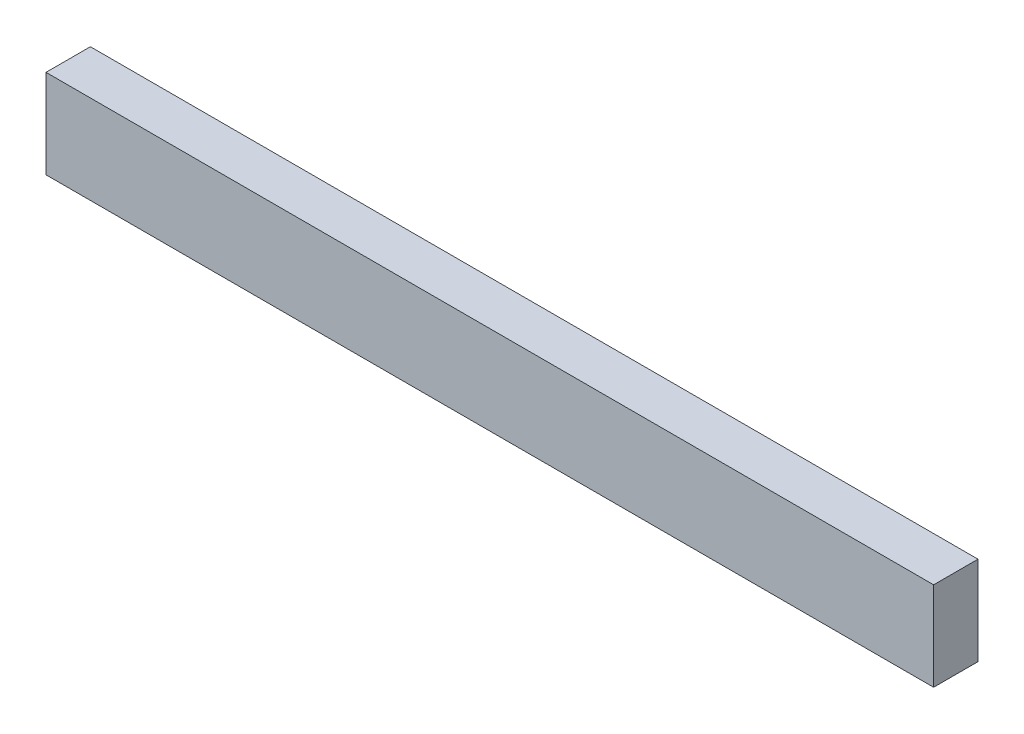
SolidWorks part; units mm, degrees
ref_plane "Front Plane" through (0, 0, 0) normal (0, 0, 1) x (1, 0, 0)
ref_plane "Top Plane" through (0, 0, 0) normal (0, 1, 0) x (1, 0, 0)
ref_plane "Right Plane" through (0, 0, 0) normal (1, 0, 0) x (0, 0, -1)
sketch "Эскиз1" plane through (0, 0, 0) normal (0, 0, 1) x (1, 0, 0)
  line L1 (-10, -1) -> (10, -1)
  line L2 (-10, -1) -> (-10, 1)
  line L3 (-10, 1) -> (10, 1)
  line L4 (10, -1) -> (10, 1)
  line L5 (-10, -1) -> (10, 1) construction
  line L6 (-10, 1) -> (10, -1) construction
  point P0 (0, 0)
  dimension "D1" = 20
  dimension "D2" = 2
extrude "Бобышка-Вытянуть1" add sketch "Эскиз1" along normal blind 1
